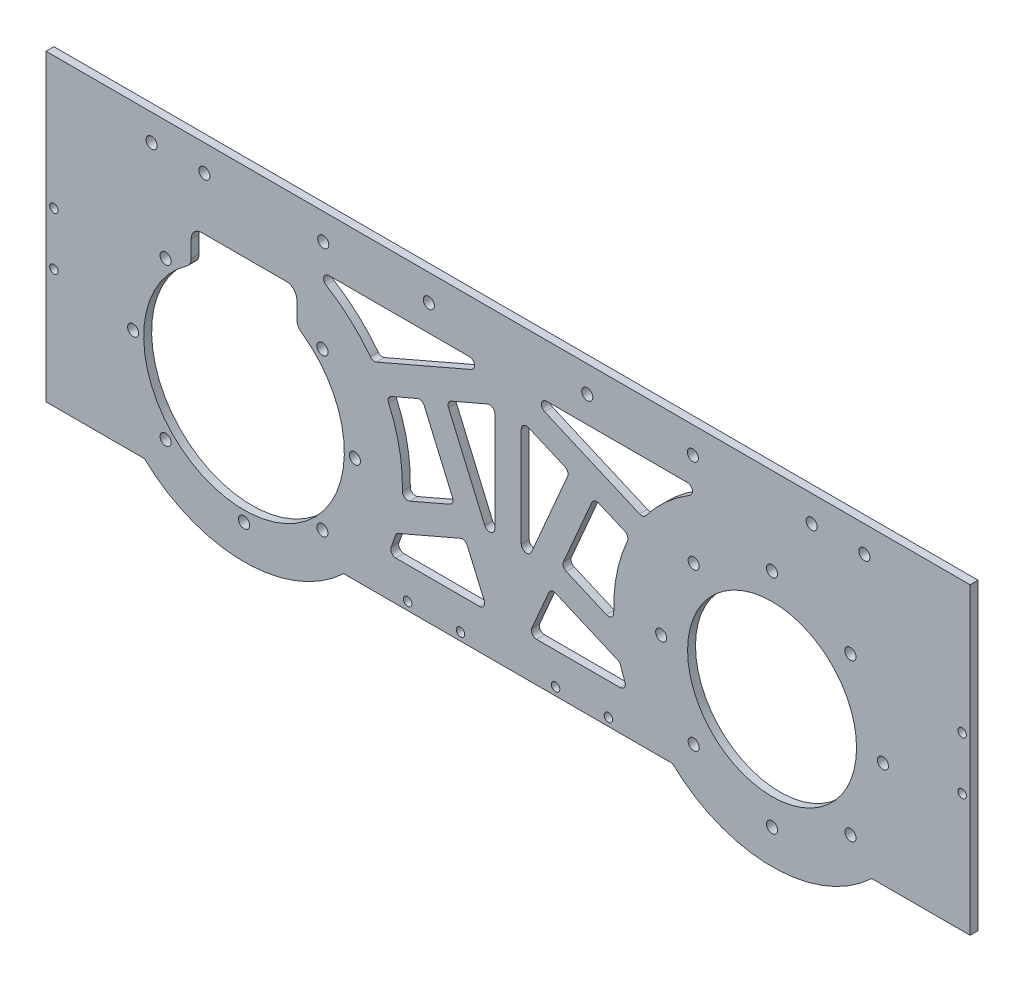
SolidWorks part; units mm, degrees
material "环氧树脂FR-4"
ref_plane "前视基准面" through (0, 0, 0) normal (0, 0, 1) x (1, 0, 0)
ref_plane "上视基准面" through (0, 0, 0) normal (0, 1, 0) x (1, 0, 0)
ref_plane "右视基准面" through (0, 0, 0) normal (1, 0, 0) x (0, 0, -1)
sketch "草图1" plane through (0, 0, 0) normal (0, 0, 1) x (1, 0, 0)
  line L1 (-175, 75) -> (175, 75)
  line L2 (-175, 75) -> (-175, -55)
  line L3 (-175, -55) -> (175, -55)
  line L4 (175, 75) -> (175, -55)
  dimension "D1" = 175
  dimension "D2" = 350
  dimension "D3" = 75
  dimension "D4" = 130
extrude "凸台-拉伸1" add sketch "草图1" along normal blind 3
sketch "草图2" plane through (0, 0, 0) normal (0, 0, -1) x (-1, 0, 0)
  line L2 (0, 55) -> (0, -55) construction
  circle A0 centre (-100, 0) radius 42 construction
  circle A1 centre (-100, 42) radius 2.1
  circle A2 centre (-70.3015, 29.6985) radius 2.1
  circle A3 centre (-58, 0) radius 2.1
  circle A4 centre (-70.3015, -29.6985) radius 2.1
  circle A5 centre (-100, -42) radius 2.1
  circle A6 centre (-129.6985, -29.6985) radius 2.1
  circle A7 centre (-142, 0) radius 2.1
  circle A8 centre (-129.6985, 29.6985) radius 2.1
  circle A10 centre (129.6985, 29.6985) radius 2.1
  circle A11 centre (142, 0) radius 2.1
  circle A12 centre (129.6985, -29.6985) radius 2.1
  circle A13 centre (100, -42) radius 2.1
  circle A14 centre (70.3015, -29.6985) radius 2.1
  circle A15 centre (58, 0) radius 2.1
  circle A16 centre (70.3015, 29.6985) radius 2.1
  circle A17 centre (100, 42) radius 2.1
  circle A18 centre (100, 0) radius 42 construction
  point P0 (0, 0)
  point P1 (-100, 0)
  point P42 (100, 0)
  dimension "D5" = 84
  dimension "D6" = 4.2
  dimension "D4" = 100
  dimension "D3" = 2
  dimension "D7" = 8
extrude "切除-拉伸1" cut sketch "草图2" against normal through all
sketch "草图3" plane through (0, 0, 0) normal (0, 0, -1) x (-1, 0, 0)
  circle A0 centre (-100, 0) radius 32
  circle A17 centre (100, 0) radius 38
  point P0 (0, 0)
  point P1 (-100, 0)
  point P3 (100, 0)
  dimension "D5" = 64
  dimension "D6" = 76
  dimension "D2" = 100
  dimension "D4" = 100
  dimension "D1" = 2
  dimension "D3" = 2
extrude "切除-拉伸3" cut sketch "草图3" against normal blind 10
sketch "草图4" plane through (0, 0, 0) normal (0, 0, -1) x (-1, 0, 0)
  line L0 (-175, 75) -> (175, 75) construction
  line L1 (80, 45) -> (120, 45)
  line L2 (80, 45) -> (80, 30)
  line L3 (80, 30) -> (120, 30)
  line L4 (120, 45) -> (120, 30)
  circle A0 centre (100, 42) radius 2.1 construction
  point P7 (100, 45)
  dimension "D1" = 30
  dimension "D2" = 0
  dimension "D3" = 40
  dimension "D4" = 15
extrude "切除-拉伸4" cut sketch "草图4" against normal through all
sketch "草图7" plane through (0, 0, 3) normal (0, 0, 1) x (1, 0, 0)
  line L0 (175, 75) -> (-175, 75) construction
  line L1 (-175, 75) -> (-175, -55) construction
  point P0 (-30, 65)
  point P4 (-70, 65)
  point P5 (-135, 65)
  point P8 (-115, 65)
  dimension "D1" = 10
  dimension "D2" = 30
  dimension "D4" = 40
  dimension "D5" = 40
  dimension "D6" = 10
  dimension "D8" = 20
  dimension "D3" = 2
  dimension "D7" = 2
hole_wizard "Ø4.2 (4.2) 直径孔1" positions "3D草图1" profile "草图8" hole size "Ø4.2" standard "GB" end condition through all
sketch3d "3D草图1"
  point P0 (-30, 65, 3)
  point P3 (-70, 65, 3)
  point P6 (-115, 65, 3)
  point P9 (-135, 65, 3)
sketch "草图8" plane through (-30, 65, 3) normal (1, 0, 0) x (0, -1, 0)
  line L0 (0, 0) -> (0, 3)
  line L1 (0, 3) -> (2.1, 3)
  line L2 (2.1, 3) -> (2.1, 0)
  line L5 (2.1, 0) -> (0, 0)
  line L11 (0, -6.35) -> (0, 107.95) construction
  dimension "通孔孔直径" = 4.2
  dimension "通孔孔深度" = 3
mirror "镜向1" about plane through (0, 0, 0) normal (1, 0, 0) of "Ø4.2 (4.2) 直径孔1"
sketch "草图9" plane through (0, 0, 3) normal (0, 0, 1) x (1, 0, 0)
  line L2 (-175, 75) -> (-175, -55) construction
  line L3 (175, 75) -> (-175, 75) construction
  point P5 (-172, 25)
  point P6 (-172, 5)
  dimension "D1" = 3
  dimension "D2" = 50
  dimension "D4" = 20
  dimension "D3" = 2
hole_wizard "Ø3.2 (3.2) 直径孔2" positions "3D草图3" profile "草图11" hole size "Ø3.2" standard "GB" end condition through all
sketch3d "3D草图3"
  point P0 (-172, 25, 3)
  point P3 (-172, 5, 3)
sketch "草图11" plane through (-172, 25, 3) normal (1, 0, 0) x (0, -1, 0)
  line L0 (0, 0) -> (0, 3)
  line L1 (0, 3) -> (1.6, 3)
  line L2 (1.6, 3) -> (1.6, 0)
  line L5 (1.6, 0) -> (0, 0)
  line L11 (0, -6.35) -> (0, 107.95) construction
  dimension "通孔孔直径" = 3.2
  dimension "通孔孔深度" = 3
mirror "镜向3" about plane through (0, 0, 0) normal (1, 0, 0) of "Ø3.2 (3.2) 直径孔2"
sketch "草图12" plane through (0, 0, 3) normal (0, 0, 1) x (1, 0, 0)
  line L0 (175, -55) -> (175, 75) construction
  line L1 (-175, -55) -> (-100, -55)
  line L2 (-175, -55) -> (-175, -40)
  line L3 (-175, -40) -> (-137.7492, -40)
  line L4 (175, -55) -> (175, -40)
  line L6 (137.7492, -40) -> (175, -40)
  line L7 (100, -55) -> (175, -55)
  arc A0 (-137.7492, -40) -> (-100, -55) centre (-100, 0) ccw
  arc A1 (100, -55) -> (137.7492, -40) centre (100, 0) ccw
  dimension "D2" = 110
  dimension "D3" = 15
  dimension "D1" = 15
extrude "切除-拉伸5" cut sketch "草图12" against normal through all
sketch "草图14" plane through (0, 0, 3) normal (0, 0, 1) x (1, 0, 0)
  line L0 (-62.2508, -40) -> (62.2508, -40)
  line L1 (-100, -55) -> (100, -55) construction
  line L2 (-100, -55) -> (100, -55)
  arc A2 (-62.2508, -40) -> (-100, -55) centre (-100, 0) cw
  arc A3 (62.2508, -40) -> (100, -55) centre (100, 0) ccw
  arc A4 (100, -55) -> (137.7492, -40) centre (100, 0) ccw construction
  dimension "D1" = 55
  dimension "D2" = 15
extrude "切除-拉伸6" cut sketch "草图14" against normal through all
fillet "圆角1" radius 4 4 edges at (-120, 32.311, 1.5) (-80, 32.311, 1.5) (-80, 45, 1.5) (-120, 45, 1.5)
sketch "草图16" plane through (0, 0, 3) normal (0, 0, 1) x (1, 0, 0)
  line L1 (76.0208, 55) -> (5, 55)
  line L20 (175, 75) -> (-175, 75) construction
  line L22 (5, 55) -> (51.266, 35)
  line L24 (0, -55) -> (0, 55) construction
  line L25 (46.0919, 26.3423) -> (32.5372, 32.2018)
  line L26 (32.5372, 32.2018) -> (20.2061, 3.6763)
  line L27 (20.2061, 3.6763) -> (40.2061, -4.9693)
  line L28 (5, 44.1057) -> (5, -6.2982)
  line L29 (5, -6.2982) -> (23.3581, 36.1697)
  line L30 (23.3581, 36.1697) -> (5, 44.1057)
  line L31 (42.404, -16.8138) -> (16.2382, -5.5028)
  line L32 (16.2382, -5.5028) -> (7.8099, -25)
  line L33 (7.8099, -25) -> (45.4564, -25)
  line L34 (62.2508, -40) -> (-62.2508, -40) construction
  arc A1 (76.0208, 55) -> (51.266, 35) centre (100, 0) ccw
  arc A3 (42.404, -16.8138) -> (45.4564, -25) centre (100, 0) ccw
  arc A4 (46.0919, 26.3423) -> (40.2061, -4.9693) centre (100, 0) ccw
  dimension "D1" = 120
  dimension "D3" = 5
  dimension "D2" = 20
  dimension "D4" = 10
  dimension "D5" = 20
  dimension "D6" = 10
  dimension "D7" = 20
  dimension "D9" = 20
  dimension "D8" = 10
  dimension "D10" = 10
  dimension "D11" = 10
  dimension "D12" = 15
extrude "切除-拉伸7" cut sketch "草图16" against normal through all
fillet "圆角2" radius 2 14 edges at (16.2382, -5.5028, 1.5) (42.404, -16.8138, 1.5) (45.4564, -25, 1.5) (7.8099, -25, 1.5) (20.2061, 3.6763, 1.5) (40.2061, -4.9693, 1.5) (5, -6.2982, 1.5) (5, 44.1057, 1.5) (32.5372, 32.2018, 1.5) (46.0919, 26.3423, 1.5) (23.3581, 36.1697, 1.5) (5, 55, 1.5) (51.266, 35, 1.5) (76.0208, 55, 1.5)
mirror "镜向4" about plane through (0, 0, 0) normal (1, 0, 0) of "圆角2", "切除-拉伸7"
sketch "草图17" plane through (0, 0, 3) normal (0, 0, 1) x (1, 0, 0)
  line L0 (62.2508, -40) -> (-62.2508, -40) construction
  line L1 (0, -1.65) -> (0, 1.65) construction
  point P0 (18, -37)
  point P5 (38, -37)
  dimension "D1" = 3
  dimension "D2" = 18
  dimension "D4" = 20
  dimension "D3" = 2
hole_wizard "Ø3.2 (3.2) 直径孔3" positions "3D草图4" profile "草图18" hole size "Ø3.2" standard "GB" end condition through all
sketch3d "3D草图4"
  point P0 (18, -37, 3)
  point P3 (38, -37, 3)
sketch "草图18" plane through (18, -37, 3) normal (1, 0, 0) x (0, -1, 0)
  line L0 (0, 0) -> (0, 3)
  line L1 (0, 3) -> (1.6, 3)
  line L2 (1.6, 3) -> (1.6, 0)
  line L5 (1.6, 0) -> (0, 0)
  line L11 (0, -6.35) -> (0, 107.95) construction
  dimension "通孔孔直径" = 3.2
  dimension "通孔孔深度" = 3
mirror "镜向5" about plane through (0, 0, 0) normal (1, 0, 0) of "Ø3.2 (3.2) 直径孔3"
